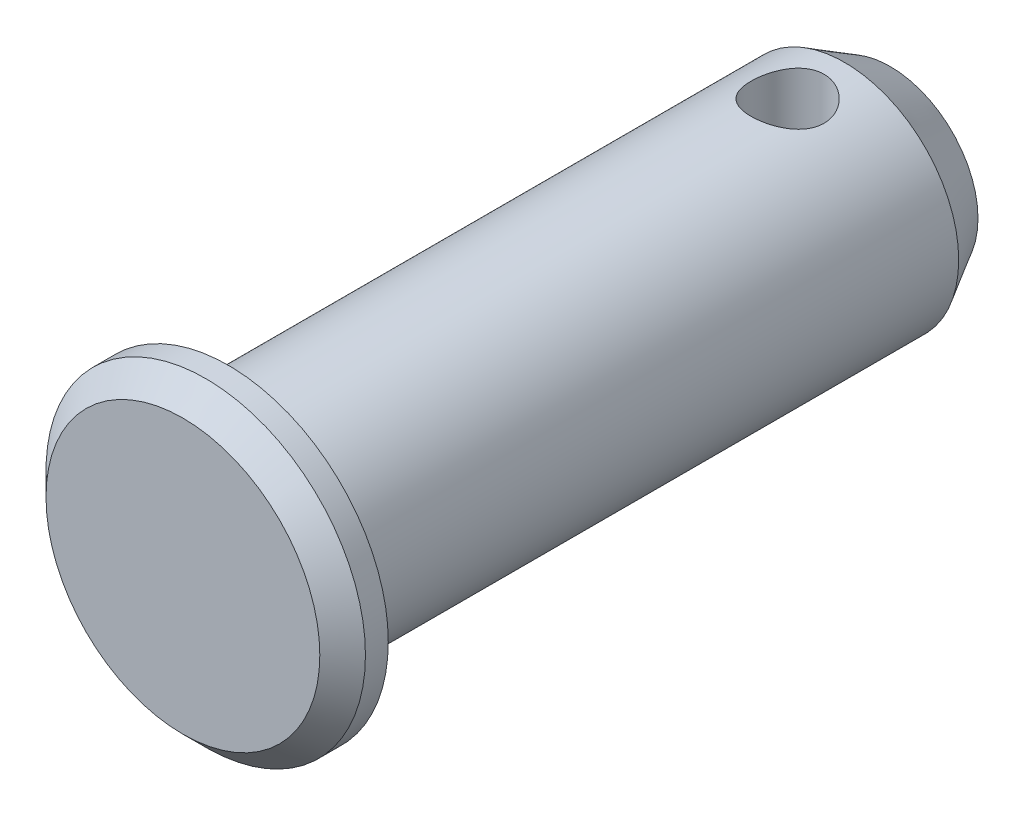
SolidWorks part; units mm, degrees
material "1.0545 (S355N)"
ref_plane "Płaszczyzna przednia" through (0, 0, 0) normal (0, 0, 1) x (1, 0, 0)
ref_plane "Płaszczyzna górna" through (0, 0, 0) normal (0, 1, 0) x (1, 0, 0)
ref_plane "Płaszczyzna prawa" through (0, 0, 0) normal (1, 0, 0) x (0, 0, -1)
sketch "Szkic1" plane through (0, 0, 0) normal (0, 1, 0) x (1, 0, 0)
  line L0 (6, -15.5) -> (-6, -15.5)
  line L1 (-7, -14.5) -> (-7, -13.5)
  line L2 (-7, -13.5) -> (-5, -13.5)
  line L3 (-5, -13.5) -> (-5, 13.5)
  line L4 (-3.8453, 15.5) -> (3.8453, 15.5)
  line L5 (5, 13.5) -> (5, -13.5)
  line L6 (5, -13.5) -> (7, -13.5)
  line L7 (7, -13.5) -> (7, -14.5)
  line L8 (7, -14.5) -> (6, -15.5)
  line L9 (-6, -15.5) -> (-7, -14.5)
  line L10 (3.8453, 15.5) -> (5, 13.5)
  line L11 (-5, 13.5) -> (-3.8453, 15.5)
  line L12 (0, -15.5) -> (0, 15.5)
  point P0 (7, -15.5)
  point P1 (-7, -15.5)
  point P5 (-5, 15.5)
  point P6 (5, 15.5)
  point P7 (0, 0)
  point P17 (0, 15.5)
  point P19 (0, -15.5)
  dimension "D1" = 14
  dimension "D2" = 10
  dimension "D3" = 2
  dimension "D4" = 30
  dimension "D8" = 30
  dimension "D9" = 29
  dimension "D10" = 2
revolve "Obrót1" add sketch "Szkic1" angle 360 about L12
sketch "Szkic2" plane through (0, 0, 0) normal (0, 1, 0) x (1, 0, 0)
  line L0 (5, -13.5) -> (-5, -13.5) construction
  circle A0 centre (0, 11) radius 1.6
  dimension "D2" = 3.2
  dimension "D1" = 24.5
extrude "Wytnij-wyciągnięcie1" cut sketch "Szkic2" against normal through all both and the other way through all contours A0
